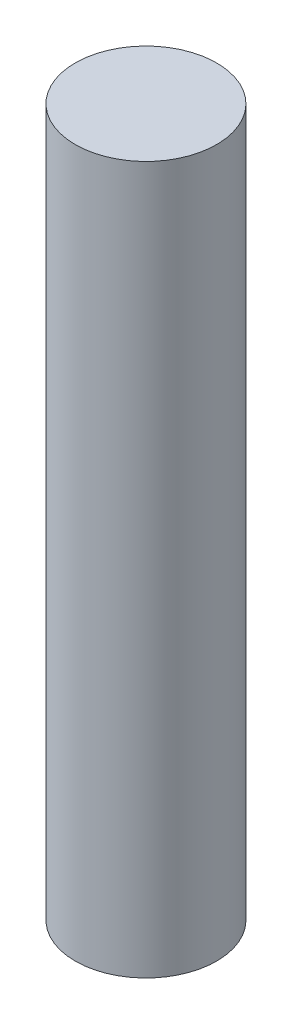
SolidWorks part; units mm, degrees
ref_plane "Plan de face" through (0, 0, 0) normal (0, 0, 1) x (1, 0, 0)
ref_plane "Plan de dessus" through (0, 0, 0) normal (0, 1, 0) x (1, 0, 0)
ref_plane "Plan de droite" through (0, 0, 0) normal (1, 0, 0) x (0, 0, -1)
sketch "Esquisse1" plane through (0, 0, 0) normal (0, 1, 0) x (1, 0, 0)
  circle A0 centre (0, 0) radius 20
  dimension "D1" = 40
extrude "Boss.-Extru.1" add sketch "Esquisse1" along normal blind 200
